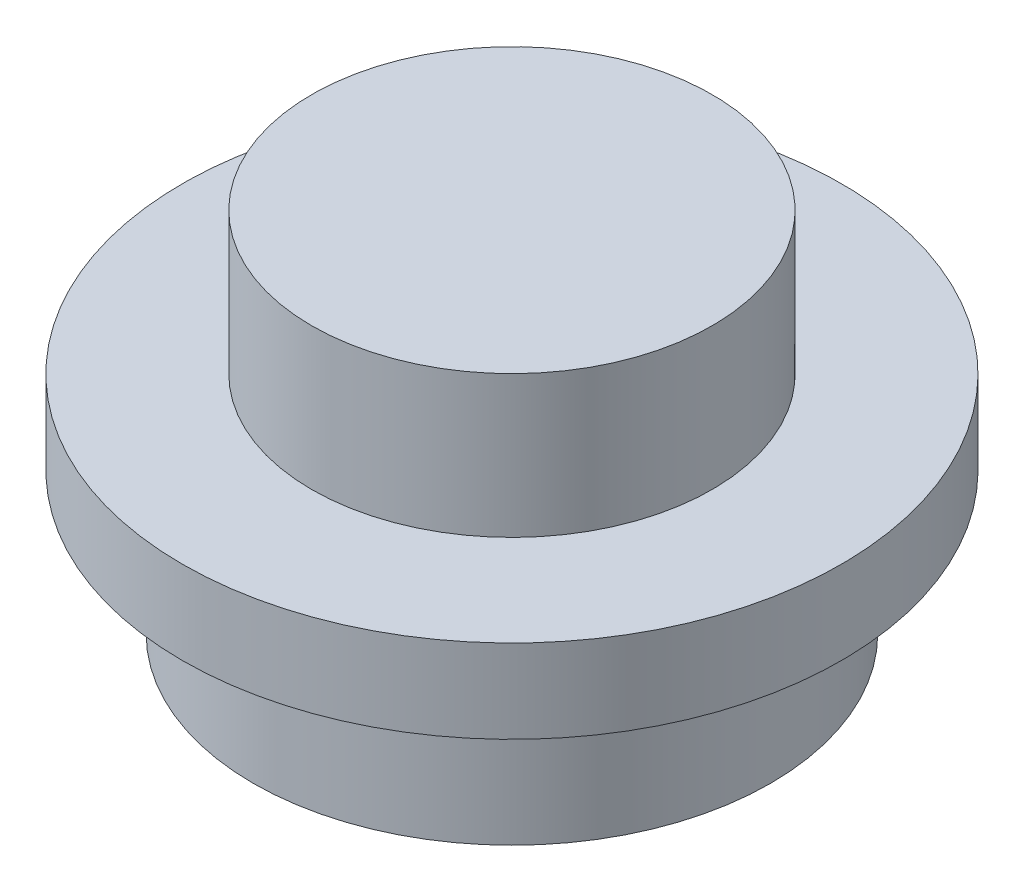
SolidWorks part; units mm, degrees
ref_plane "Front Plane" through (0, 0, 0) normal (0, 0, 1) x (1, 0, 0)
ref_plane "Top Plane" through (0, 0, 0) normal (0, 1, 0) x (1, 0, 0)
ref_plane "Right Plane" through (0, 0, 0) normal (1, 0, 0) x (0, 0, -1)
sketch "Sketch1" plane through (0, 0, 0) normal (0, 1, 0) x (1, 0, 0)
  circle A0 centre (0, 0) radius 2.4
  circle A1 centre (0, 0) radius 3.1
  dimension "D1" = 4.8
  dimension "D2" = 6.2
extrude "Boss-Extrude1" add sketch "Sketch1" along normal blind 1.7
sketch "Sketch2" plane through (0, 1.7, 0) normal (0, 1, 0) x (1, 0, 0)
  circle A0 centre (0, 0) radius 3.95
  dimension "D1" = 7.9
extrude "Boss-Extrude2" add sketch "Sketch2" along normal blind 1
sketch "Sketch3" plane through (0, 2.7, 0) normal (0, 1, 0) x (1, 0, 0)
  circle A0 centre (0, 0) radius 2.4
  dimension "D1" = 4.8
extrude "Boss-Extrude3" add sketch "Sketch3" along normal blind 1.7
